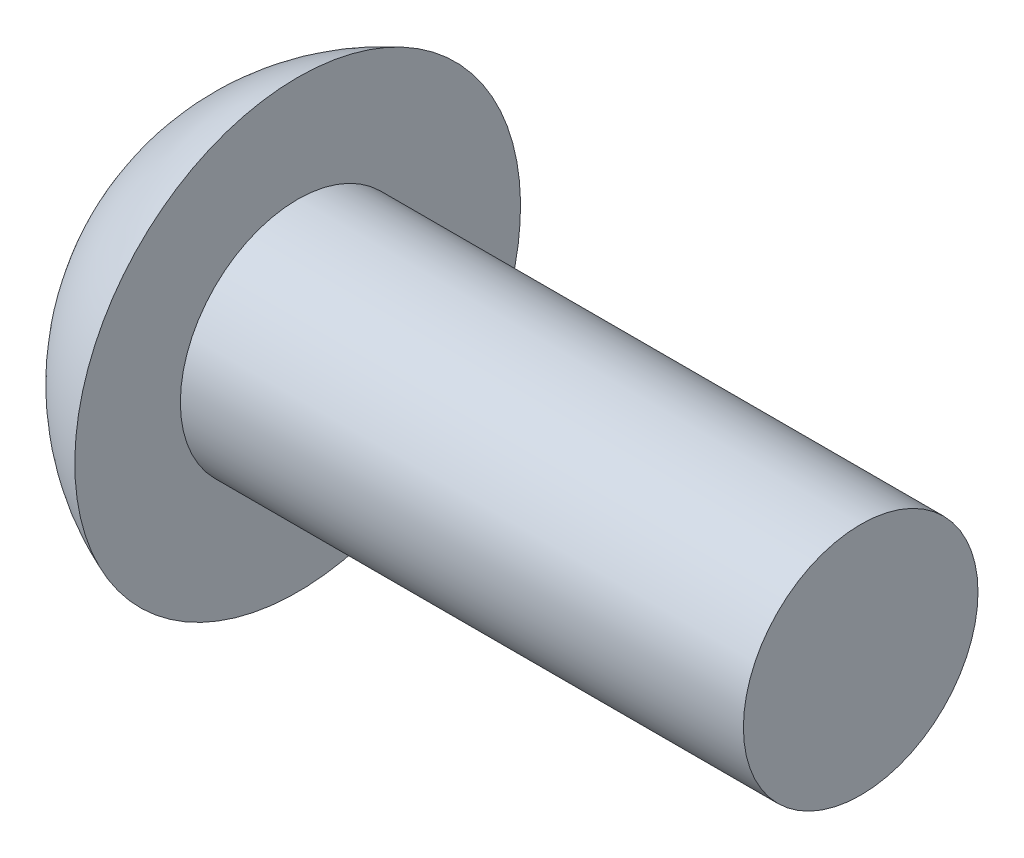
SolidWorks part; units mm, degrees
ref_plane "Front" through (0, 0, 0) normal (0, 0, 1) x (1, 0, 0)
ref_plane "Top" through (0, 0, 0) normal (0, 1, 0) x (1, 0, 0)
ref_plane "Right" through (0, 0, 0) normal (1, 0, 0) x (0, 0, -1)
sketch "Sketch1" plane through (0, 0, 0) normal (1, 0, 0) x (0, 0, -1)
  line L0 (0, 0) -> (1.6, 0) construction
  circle A0 centre (0, 0) radius 4.75
  dimension "dk" = 9.5
  dimension "a" = 1.6
extrude "BaseHead" add sketch "Sketch1" along normal blind 2.75
sketch "Sketch2" plane through (2.75, 0, 0) normal (1, 0, 0) x (0, 0, -1)
  circle A0 centre (0, 0) radius 2.5
  dimension "d" = 5
extrude "BaseBody" add sketch "Sketch2" along normal blind 12
cosmetic thread "ThreadCosmetic1" [suppressed] parameters "D1"=10.4, "THD_MINOR"=4.134
fillet "HeadFillet" [suppressed] radius 0.2
sketch "Sketch3" plane through (-13.4796, 2.4796, 0) normal (0, 0, 1) x (0, -1, 0)
  line L0 (2.4796, 13.4796) -> (2.4796, 41.0387) construction
  line L3 (-2.2704, 13.4796) -> (2.4796, 13.4796) construction
  line L5 (-7.2704, 16.2296) -> (-7.2704, 8.4796)
  line L6 (0.2596, 13.4796) -> (0.2596, 8.4796)
  line L7 (0.2596, 8.4796) -> (-7.2704, 8.4796)
  line L8 (-7.2704, 16.2296) -> (-2.2704, 16.2296)
  line L9 (-2.2704, 13.4796) -> (7.2296, 13.4796) construction
  arc A0 (-2.2704, 16.2296) -> (0.2596, 13.4796) centre (2.4796, 18.0608) ccw
  dimension "D2" = 5
  dimension "e" = 4.44
  dimension "D3" = 5
revolve "Cut-Revolve1" cut sketch "Sketch3" angle 360 about L0
sketch "Sketch4" plane through (0, 0, 0) normal (1, 0, 0) x (0, 0, -1)
  line L1 (1.7321, 0) -> (0.866, 1.5)
  line L2 (0.866, 1.5) -> (-0.866, 1.5)
  line L3 (-0.866, 1.5) -> (-1.7321, 0)
  line L4 (-1.7321, 0) -> (-0.866, -1.5)
  line L5 (-0.866, -1.5) -> (0.866, -1.5)
  line L6 (0.866, -1.5) -> (1.7321, 0)
  circle A0 centre (0, 0) radius 1.5 construction
  dimension "s" = 3
extrude "HexagonSocket" cut sketch "Sketch4" along normal blind 1.56
sketch "Sketch5" plane through (1.56, 0, 0) normal (-1, 0, 0) x (0, 0, 1)
  line L0 (0.866, -1.5) -> (-0.866, -1.5) construction
  line L1 (-0.866, -1.5) -> (-1.7321, 0) construction
  line L2 (1.7321, 0) -> (0.866, -1.5) construction
  line L3 (0.866, 1.5) -> (1.7321, 0) construction
  line L4 (-1.7321, 0) -> (-0.866, 1.5) construction
  line L5 (-0.866, 1.5) -> (0.866, 1.5) construction
  line L6 (0.866, -1.5) -> (-0.866, -1.5)
  line L7 (-0.866, -1.5) -> (-1.7321, 0)
  line L8 (1.7321, 0) -> (0.866, -1.5)
  line L9 (0.866, 1.5) -> (1.7321, 0)
  line L10 (-1.7321, 0) -> (-0.866, 1.5)
  line L11 (-0.866, 1.5) -> (0.866, 1.5)
extrude "Cut-Extrude2" cut sketch "Sketch5" against normal blind 5 draft 60
sketch "Sketch6" plane through (0, 0, 0) normal (0, 0, 1) x (1, 0, 0)
  line L0 (14.75, 2.125) -> (14.9665, 2.5)
  line L1 (14.9665, 2.5) -> (14.9665, 2.933)
  line L2 (14.9665, 2.933) -> (14.5335, 2.933)
  line L3 (14.5335, 2.933) -> (14.5335, 2.5)
  line L4 (14.5335, 2.5) -> (14.75, 2.125)
  line L5 (0, 0) -> (24.7294, 0) construction
  line L6 (14.75, -2.5) -> (14.75, 2.5) construction
  dimension "D1" = 0.433
  dimension "D2" = 5
revolve "Cut-Revolve10" [suppressed] cut sketch "Sketch6" angle 360 about L5
pattern_linear "LPattern10" [suppressed] count 21 spacing 0.5196 along (1, 0, 0)
equation "\"D1@ThreadCosmetic1\" = \"l@BaseBody\" - \"a@Sketch1\""
equation "\"D2@Sketch6\" = \"d@Sketch2\""
equation "\"D1@Sketch6\" =  (\"d@Sketch2\" - \"THD_MINOR@ThreadCosmetic1\" )  / 2"
equation "\"D3@LPattern10\" = \"D1@Sketch6\" * 1.2"
equation "\"D1@LPattern10\" = \"D1@ThreadCosmetic1\" / \"D3@LPattern10\" + 1"
